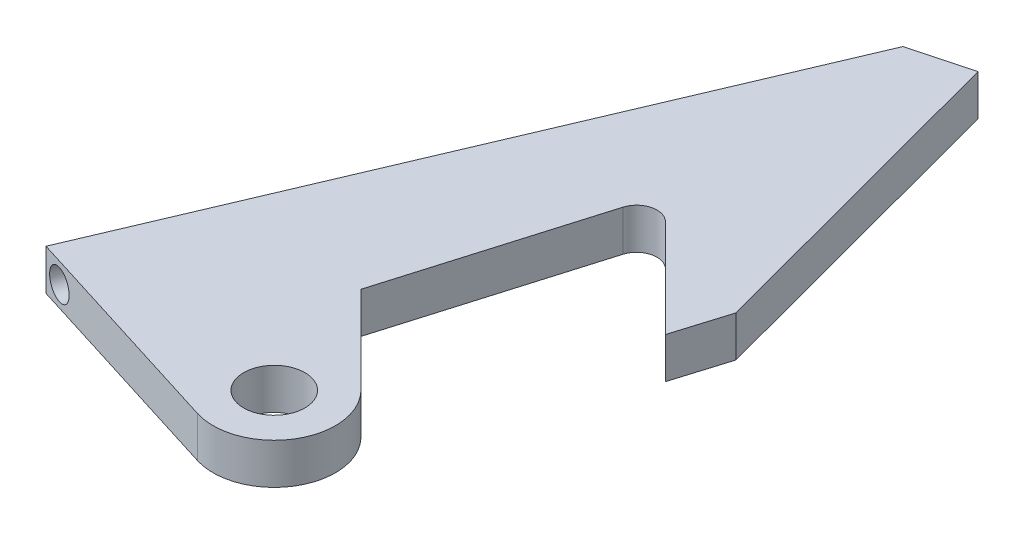
SolidWorks part; units mm, degrees
ref_plane "Front Plane" through (0, 0, 0) normal (0, 0, 1) x (1, 0, 0)
ref_plane "Top Plane" through (0, 0, 0) normal (0, 1, 0) x (1, 0, 0)
ref_plane "Right Plane" through (0, 0, 0) normal (1, 0, 0) x (0, 0, -1)
sketch "Sketch1" plane through (0, 0, 0) normal (0, 1, 0) x (1, 0, 0)
  line L14 (-2.7155, -50.4526) -> (-16.4492, -36.7162)
  line L15 (-0.2503, -64.2218) -> (8.9811, -34.0664) construction
  line L16 (-33.45, -172.6721) -> (154.2855, 440.5857) construction
  line L17 (-1.4647, -63.85) -> (7.7667, -33.6946) construction
  line L18 (-10.7741, -61.0002) -> (-1.5427, -30.8448) construction
  line L20 (-7.1439, -5.3021) -> (-16.4492, -36.7162)
  line L21 (13.3156, -19.1289) -> (-1.8546, -3.9587)
  line L24 (-12.3816, -66.1571) -> (-46.728, -55.3998)
  line L27 (15.8795, -10.7537) -> (2.2198, 40.5612)
  line L30 (-46.728, -55.3998) -> (-6.9942, 38.1085)
  line L31 (-6.9942, 38.1085) -> (2.2198, 40.5612)
  line L32 (13.3156, -19.1289) -> (15.8795, -10.7537)
  circle A4 centre (-9.5834, -57.0524) radius 4.7625
  arc A5 (-12.3816, -66.1571) -> (-2.7155, -50.4526) centre (-9.5834, -57.0524) ccw
  arc A8 (-1.8546, -3.9587) -> (-7.1439, -5.3021) centre (-4.0997, -6.2038) ccw
  circle A9 centre (-9.5834, -57.0524) radius 37.1814 construction
  point P27 (-5.6282, -0.1851)
  dimension "D2" = 38.1
  dimension "D1" = 1.27
  dimension "D3" = 74.3628
extrude "Boss-Extrude1" add sketch "Sketch1" along normal blind 6.35
sketch "Sketch2" plane through (-19.9756, 0, 63.7787) normal (-0.2989, 0, 0.9543) x (0.9543, 0, 0.2989)
  line L0 (-28.0339, 3.175) -> (-24.8589, 3.175) construction
  line L3 (-28.0339, 6.35) -> (-28.0339, 0) construction
  dimension "D1" = 3.175
hole_wizard "#14 (0.182) Diameter Hole1" positions "Sketch3" profile "Sketch4" hole size "#14" standard "ANSI Inch"
sketch "Sketch3" plane through (-19.9756, 0, 63.7787) normal (-0.2989, 0, 0.9543) x (0.9543, 0, 0.2989)
  point P0 (-24.8589, 3.175)
sketch "Sketch4" plane through (-43.6982, 3.175, 56.3487) normal (0, 1, 0) x (0.9543, 0, 0.2989)
  line L0 (0, 0) -> (0, 7.7388)
  line L1 (0, 7.7388) -> (2.3114, 6.35)
  line L2 (2.3114, 6.35) -> (2.3114, 0)
  line L5 (2.3114, 0) -> (0, 0)
  line L10 (0, 7.7388) -> (-2.3114, 6.35) construction
  line L11 (0, -6.35) -> (0, 107.95) construction
  dimension "Hole Dia." = 4.6228
  dimension "Hole Depth" = 6.35
  dimension "Drill Angle" = 118
